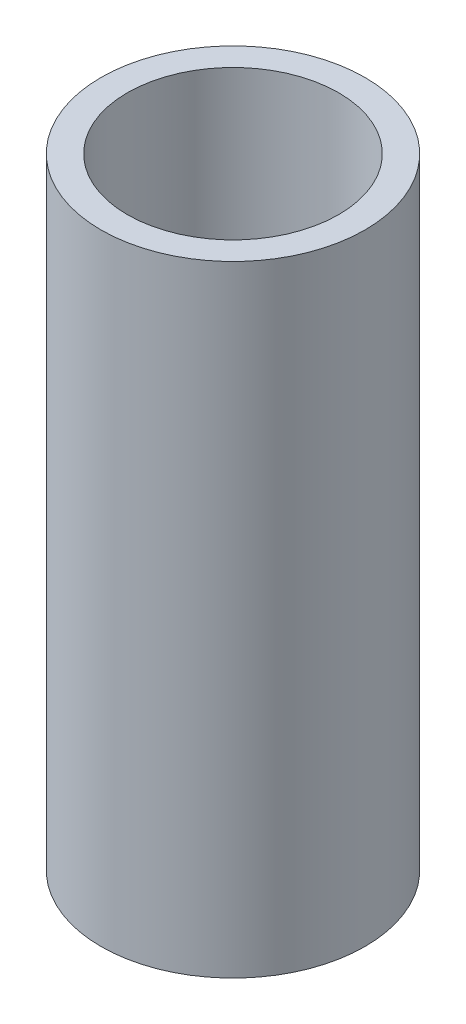
SolidWorks part; units mm, degrees
ref_plane "Front Plane" through (0, 0, 0) normal (0, 0, 1) x (1, 0, 0)
ref_plane "Top Plane" through (0, 0, 0) normal (0, 1, 0) x (1, 0, 0)
ref_plane "Right Plane" through (0, 0, 0) normal (1, 0, 0) x (0, 0, -1)
sketch "Sketch2" plane through (0, 0, 0) normal (0, 1, 0) x (1, 0, 0)
  circle A0 centre (0, 0) radius 50.8
  circle A1 centre (0, 0) radius 63.5
  dimension "D1" = 101.6
extrude "Boss-Extrude1" add sketch "Sketch2" along normal blind 298.45
